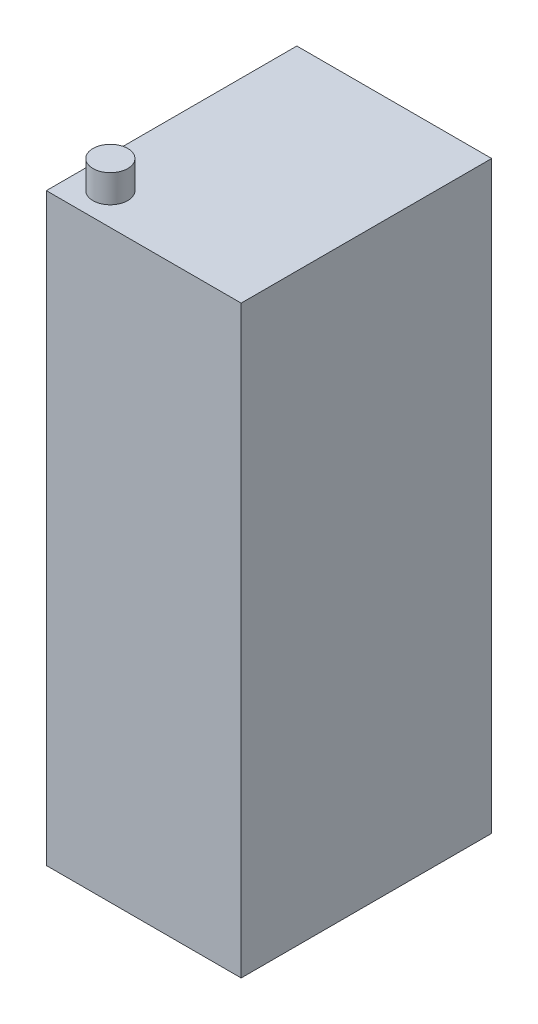
SolidWorks part; units mm, degrees
ref_plane "Front Plane" through (0, 0, 0) normal (0, 0, 1) x (1, 0, 0)
ref_plane "Top Plane" through (0, 0, 0) normal (0, 1, 0) x (1, 0, 0)
ref_plane "Right Plane" through (0, 0, 0) normal (1, 0, 0) x (0, 0, -1)
sketch "Sketch1" plane through (0, 0, 0) normal (0, 0, 1) x (1, 0, 0)
  line L1 (-121.4577, 150.5589) -> (-51.4577, 150.5589)
  line L2 (-121.4577, 150.5589) -> (-121.4577, -59.4411)
  line L3 (-121.4577, -59.4411) -> (-51.4577, -59.4411)
  line L4 (-51.4577, 150.5589) -> (-51.4577, -59.4411)
  line L5 (-121.4577, 150.5589) -> (-51.4577, -59.4411) construction
  line L6 (-121.4577, -59.4411) -> (-51.4577, 150.5589) construction
  point P0 (-86.4577, 45.5589)
  dimension "D1" = 210
  dimension "D2" = 70
extrude "LV Battry" add sketch "Sketch1" along normal blind 90
sketch "Sketch2" plane through (0, 150.5589, 0) normal (0, 1, 0) x (1, 0, 0)
  line L0 (-121.4577, -90) -> (-121.4577, 0) construction
  line L1 (-51.4577, -90) -> (-121.4577, -90) construction
  circle A0 centre (-109.9577, -78.5) radius 6.25
  dimension "D1" = 12.5
  dimension "D2" = 11.5
  dimension "D3" = 11.5
extrude "Cables (3x 14AWG)" add sketch "Sketch2" along normal blind 10
